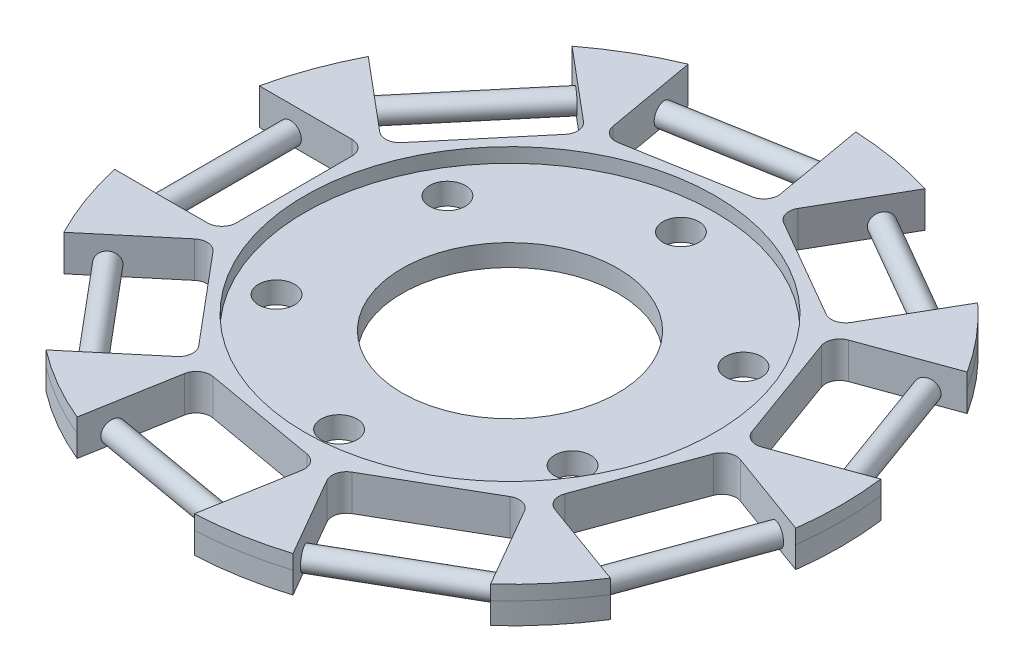
SolidWorks part; units mm, degrees
ref_plane "正面" through (0, 0, 0) normal (0, 0, 1) x (1, 0, 0)
ref_plane "平面" through (0, 0, 0) normal (0, 1, 0) x (1, 0, 0)
ref_plane "右側面" through (0, 0, 0) normal (1, 0, 0) x (0, 0, -1)
sketch "ｽｹｯﾁ1" plane through (0, 0, 0) normal (0, 0, 1) x (1, 0, 0)
  line L0 (0, 0) -> (0, 65.6982) construction
  line L1 (-15, -3.4846) -> (-15, -0.4846)
  line L2 (-15, -0.4846) -> (-28.5, -0.4846)
  line L3 (-28.5, -0.4846) -> (-28.5, 1.5154)
  line L4 (-28.5, 1.5154) -> (-46, 1.5154)
  line L5 (-46, 1.5154) -> (-46, -0.4846)
  line L6 (-46, -5.4846) -> (-28.5, -5.4846)
  line L7 (-28.5, -5.4846) -> (-28.5, -3.4846)
  line L8 (-28.5, -3.4846) -> (-15, -3.4846)
  line L9 (-46, -0.4846) -> (-45.9999, -0.4846)
  line L10 (-45.9999, -0.4846) -> (-45.9999, -3.4846)
  line L11 (-45.9999, -3.4846) -> (-46, -3.4846)
  line L12 (-46, -3.4846) -> (-46, -5.4846)
  dimension "D1" = 15
  dimension "D2" = 28.5
  dimension "D3" = 3
  dimension "D4" = 7
  dimension "D5" = 2
  dimension "D6" = 17.5
  dimension "D7" = 3
  dimension "D8" = 2
  dimension "D9" = 0.0001
revolve "回転1" add sketch "ｽｹｯﾁ1" angle 360 about L0
sketch "ｽｹｯﾁ2" plane through (0, -0.4846, 0) normal (0, 1, 0) x (1, 0, 0)
  circle A0 centre (0, 23.75) radius 2.5
  circle A1 centre (20.5681, 11.875) radius 2.5
  circle A2 centre (20.5681, -11.875) radius 2.5
  circle A3 centre (0, -23.75) radius 2.5
  circle A4 centre (-20.5681, -11.875) radius 2.5
  circle A5 centre (-20.5681, 11.875) radius 2.5
  point P16 (0, 0)
  dimension "D1" = 23.75
  dimension "D2" = 5
  dimension "D3" = 6
extrude "ｶｯﾄ - 押し出し1" cut sketch "ｽｹｯﾁ2" against normal blind 10
sketch "ｽｹｯﾁ3" plane through (0, 1.5154, 0) normal (0, 1, 0) x (1, 0, 0)
  line L1 (0, 23.75) -> (20.5681, 11.875) construction
  line L2 (21.9715, 21.9558) -> (8.0285, 30.0058)
  line L3 (24.7036, 22.6878) -> (38.5557, 46.6805)
  line L4 (7.2964, 32.7378) -> (21.1486, 56.7305)
  line L5 (38.5557, 46.6805) -> (21.1486, 56.7305)
  line L6 (23.7036, 20.9558) -> (21.1486, 56.7305) construction
  line L7 (6.2964, 31.0058) -> (38.5557, 46.6805) construction
  line L8 (33.5075, 1.5007) -> (59.5411, 10.9762)
  line L9 (30.944, 2.6961) -> (25.4375, 17.8251)
  line L10 (26.6329, 20.3886) -> (52.6665, 29.864)
  line L11 (59.5411, 10.9762) -> (52.6665, 29.864)
  line L12 (26.6329, -20.3886) -> (52.6665, -29.864)
  line L13 (25.4375, -17.8251) -> (30.944, -2.6961)
  line L14 (33.5075, -1.5007) -> (59.5411, -10.9762)
  line L15 (52.6665, -29.864) -> (59.5411, -10.9762)
  line L16 (7.2964, -32.7378) -> (21.1486, -56.7305)
  line L17 (8.0285, -30.0058) -> (21.9715, -21.9558)
  line L18 (24.7036, -22.6878) -> (38.5557, -46.6805)
  line L19 (21.1486, -56.7305) -> (38.5557, -46.6805)
  line L20 (-15.4541, -29.7687) -> (-20.2649, -57.0522)
  line L21 (-13.1371, -28.1464) -> (2.7183, -30.9421)
  line L22 (4.3406, -33.259) -> (-0.4702, -60.5425)
  line L23 (-20.2649, -57.0522) -> (-0.4702, -60.5425)
  line L24 (-30.9734, -12.8705) -> (-52.1962, -30.6785)
  line L25 (-28.1558, -13.117) -> (-17.8069, -25.4503)
  line L26 (-18.0534, -28.268) -> (-39.2762, -46.076)
  line L27 (-52.1962, -30.6785) -> (-39.2762, -46.076)
  line L28 (-32, 10.05) -> (-59.7044, 10.05)
  line L29 (-30, 8.05) -> (-30, -8.05)
  line L30 (-32, -10.05) -> (-59.7044, -10.05)
  line L31 (-59.7044, 10.05) -> (-59.7044, -10.05)
  line L32 (-18.0534, 28.268) -> (-39.2762, 46.076)
  line L33 (-17.8069, 25.4503) -> (-28.1558, 13.117)
  line L34 (-30.9734, 12.8705) -> (-52.1962, 30.6785)
  line L35 (-39.2762, 46.076) -> (-52.1962, 30.6785)
  line L36 (4.3406, 33.259) -> (-0.4702, 60.5425)
  line L37 (2.7183, 30.9421) -> (-13.1371, 28.1464)
  line L38 (-15.4541, 29.7687) -> (-20.2649, 57.0522)
  line L39 (-0.4702, 60.5425) -> (-20.2649, 57.0522)
  circle A1 centre (0, 0) radius 28.5 construction
  circle A2 centre (0, 0) radius 46
  circle A3 centre (0, 0) radius 46
  arc A4 (4.3406, 33.259) -> (2.7183, 30.9421) centre (2.371, 32.9117) cw
  arc A5 (-13.1371, 28.1464) -> (-15.4541, 29.7687) centre (-13.4844, 30.116) cw
  arc A6 (-18.0534, 28.268) -> (-17.8069, 25.4503) centre (-19.339, 26.7359) cw
  arc A7 (-28.1558, 13.117) -> (-30.9734, 12.8705) centre (-29.6879, 14.4025) cw
  arc A8 (-32, 10.05) -> (-30, 8.05) centre (-32, 8.05) cw
  arc A9 (-30, -8.05) -> (-32, -10.05) centre (-32, -8.05) cw
  arc A10 (-30.9734, -12.8705) -> (-28.1558, -13.117) centre (-29.6879, -14.4025) cw
  arc A11 (-17.8069, -25.4503) -> (-18.0534, -28.268) centre (-19.339, -26.7359) cw
  arc A12 (-15.4541, -29.7687) -> (-13.1371, -28.1464) centre (-13.4844, -30.116) cw
  arc A13 (2.7183, -30.9421) -> (4.3406, -33.259) centre (2.371, -32.9117) cw
  arc A14 (7.2964, -32.7378) -> (8.0285, -30.0058) centre (9.0285, -31.7378) cw
  arc A15 (21.9715, -21.9558) -> (24.7036, -22.6878) centre (22.9715, -23.6878) cw
  arc A16 (26.6329, -20.3886) -> (25.4375, -17.8251) centre (27.3169, -18.5092) cw
  arc A17 (30.944, -2.6961) -> (33.5075, -1.5007) centre (32.8234, -3.3801) cw
  arc A18 (33.5075, 1.5007) -> (30.944, 2.6961) centre (32.8234, 3.3801) cw
  arc A19 (25.4375, 17.8251) -> (26.6329, 20.3886) centre (27.3169, 18.5092) cw
  arc A20 (24.7036, 22.6878) -> (21.9715, 21.9558) centre (22.9715, 23.6878) cw
  arc A21 (8.0285, 30.0058) -> (7.2964, 32.7378) centre (9.0285, 31.7378) cw
  point P9 (22.4261, 38.8431)
  point P13 (15, 25.9808)
  point P51 (0, 0)
  circle M46 centre (0, 0) radius 46
  dimension "D1" = 2
  dimension "D3" = 0
  dimension "D6" = 20.1
  dimension "D7" = 30
  dimension "D2" = 0
  dimension "D8" = 9
extrude "ｶｯﾄ - 押し出し3" cut sketch "ｽｹｯﾁ3" against normal blind 10 contours A5 L37 A4 L36 L38 M46 | A21 L2 A20 L3 L4 M46 | A19 L9 A18 L8 L10 M46 | A17 L13 A16 L12 L14 M46 | A15 L17 A14 L16 L18 M46 | A13 L21 A12 L20 L22 M46 | A11 L25 A10 L24 L26 M46 | A9 L29 A8 L28 L30 M46 | A7 L33 A6 L32 L34 M46
sketch "ｽｹｯﾁ4" plane through (0, 1.5154, 0) normal (0, 1, 0) x (1, 0, 0)
  line L0 (-16.9388, 38.1888) -> (2.8559, 41.6791) construction
  line L3 (-15.4541, 29.7687) -> (-17.6922, 42.4616) construction
  line L4 (4.3406, 33.259) -> (2.1025, 45.9519) construction
  line L5 (11.5714, 40.1423) -> (28.9786, 30.0923) construction
  line L6 (34.6672, 23.3128) -> (41.5418, 4.425) construction
  line L7 (41.5418, -4.425) -> (34.6672, -23.3128) construction
  line L8 (28.9786, -30.0923) -> (11.5714, -40.1423) construction
  line L9 (2.8559, -41.6791) -> (-16.9388, -38.1888) construction
  line L10 (-24.6031, -33.7638) -> (-37.5231, -18.3663) construction
  line L11 (-40.55, -10.05) -> (-40.55, 10.05) construction
  line L12 (-37.5231, 18.3663) -> (-24.6031, 33.7638) construction
  point P26 (0, 0)
  dimension "D1" = 40.55
  dimension "D2" = 9
sketch "ｽｹｯﾁ5" plane through (-9.8973, 0, 1.7452) normal (0.9848, 0, -0.1736) x (-0.1736, 0, -0.9848)
  line L0 (40.55, 1.5154) -> (40.55, -5.4846) construction
  line L1 (32, -5.4846) -> (44.8887, -5.4846) construction
  circle A0 centre (40.55, -1.9846) radius 1.5
  dimension "D1" = 3
extrude "ﾎﾞｽ - 押し出し1" add sketch "ｽｹｯﾁ5" along normal blind 20.1
sketch3d "3Dｽｹｯﾁ1"
  line L0 (0, 0, 0) -> (0, -7.8348, 0) construction
  point P0 (0, 0, 0)
  point P4 (0, -1.9846, 0)
  dimension "D1" = 1.5
pattern_circular "円形ﾊﾟﾀｰﾝ8" count 9 over 360 about axis through (0, 0, 0) along (0, -1, 0) of "ﾎﾞｽ - 押し出し1"
sketch "ｽｹｯﾁ6" plane through (0, -5.4846, 0) normal (0, -1, 0) x (1, 0, 0)
  circle A0 centre (0, 0) radius 108.5166
extrude "ｶｯﾄ - 押し出し4" cut sketch "ｽｹｯﾁ6" against normal blind 2
